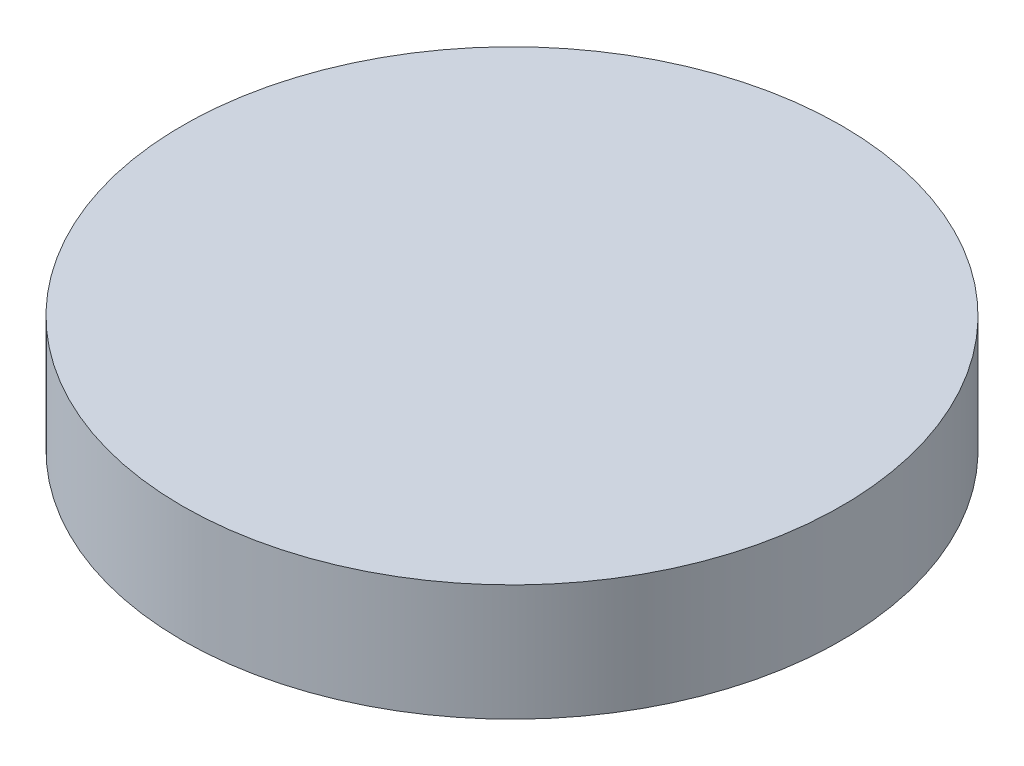
SolidWorks part; units mm, degrees
ref_plane "Front Plane" through (0, 0, 0) normal (0, 0, 1) x (1, 0, 0)
ref_plane "Top Plane" through (0, 0, 0) normal (0, 1, 0) x (1, 0, 0)
ref_plane "Right Plane" through (0, 0, 0) normal (1, 0, 0) x (0, 0, -1)
sketch "Sketch1" plane through (0, 0, 0) normal (0, 1, 0) x (1, 0, 0)
  circle A0 centre (0, 0) radius 53.975
  dimension "D1" = 107.95
extrude "Boss-Extrude1" add sketch "Sketch1" along normal blind 19.05
